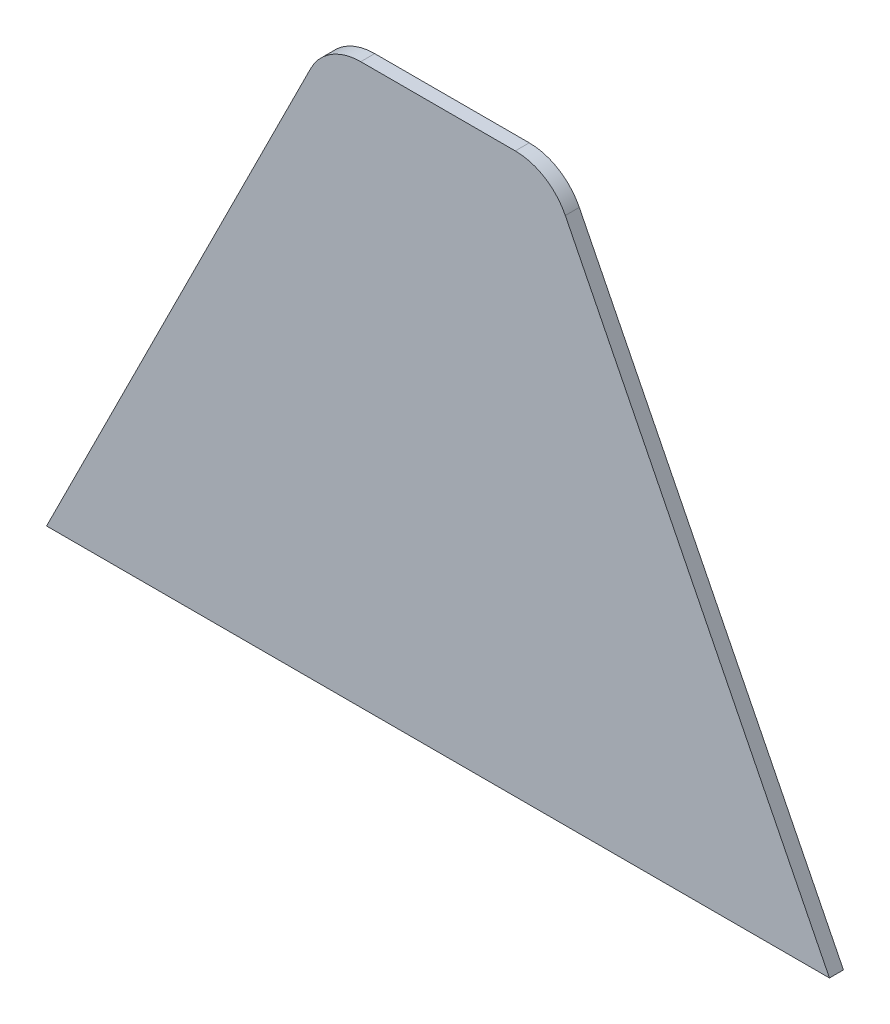
SolidWorks part; units mm, degrees
ref_plane "Front Plane" through (0, 0, 0) normal (0, 0, 1) x (1, 0, 0)
ref_plane "Top Plane" through (0, 0, 0) normal (0, 1, 0) x (1, 0, 0)
ref_plane "Right Plane" through (0, 0, 0) normal (1, 0, 0) x (0, 0, -1)
sketch "Sketch1" plane through (0, 0, 0) normal (0, 0, 1) x (1, 0, 0)
  line L0 (0, 0) -> (63.5, 127)
  line L1 (114.3, 127) -> (177.8, 0)
  line L2 (177.8, 0) -> (0, 0)
  line L3 (63.5, 127) -> (114.3, 127)
  dimension "D1" = 177.8
  dimension "D2" = 50.8
  dimension "D3" = 127
  dimension "D4" = 63.435
extrude "MainShape" add sketch "Sketch1" along normal blind 3.175
fillet "Fillet1" radius 12.7 2 edges at (114.3, 127, 1.5875) (63.5, 127, 1.5875)
